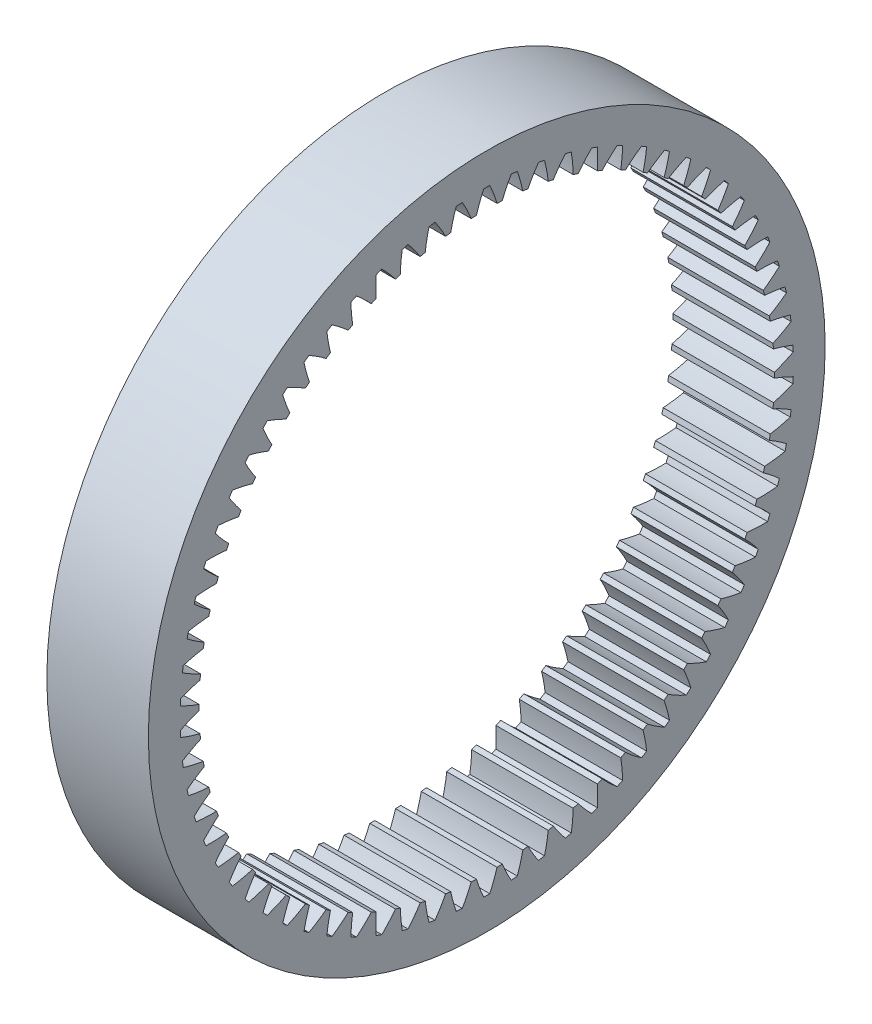
SolidWorks part; units mm, degrees
ref_plane "Plane1" through (0, 0, 0) normal (0, 0, 1) x (1, 0, 0)
ref_plane "Plane2" through (0, 0, 0) normal (0, 1, 0) x (1, 0, 0)
ref_plane "Plane3" through (0, 0, 0) normal (1, 0, 0) x (0, 0, -1)
other "Configuration Table"
sketch "HoldingSke" plane through (0, 0, 0) normal (0, 1, 0) x (1, 0, 0)
  line L0 (0, 0) -> (0.342, -0.9397)
  line L1 (-15, 0) -> (100, 0) construction
  line L2 (0, 0) -> (-2.1039, 2.3779)
  line L3 (0, 0) -> (-11.863, 4.5341)
  line L4 (0, 0) -> (2.9537, 8.1152)
  line L5 (0, 0) -> (-23.7986, -8.8762)
  line L6 (0, 0) -> (-10.5278, -7.1032)
  line L7 (-2.1039, 2.3779) -> (3.3635, 27.1825)
  line L8 (-76.2, 3.3779) -> (-54.61, 3.3779)
  line L9 (-71.009, 38.7566) -> (-53.1078, 45.2721)
  line L10 (-76.2, 71.12) -> (104.1128, 71.12)
  line L11 (0, 0) -> (-12, 0)
  line L12 (-76.2, 101.6) -> (-76.162, 101.6)
  line L13 (24.9733, 27.94) -> (52.9518, 28.4284)
  line L14 (24.9733, 27.94) -> (24.9743, 27.94)
  line L15 (24.9733, 27.94) -> (100.4006, 29.5858)
  circle A0 centre (0, 0) radius 40
  circle A1 centre (0, 0) radius 12.7
  circle A2 centre (0, 0) radius 12.7
  dimension "MHD" = 25.4
  dimension "Hub_dia" = 25.4
  dimension "Diameter" = 80
  dimension "Num_teeth" = 70
  dimension "Pitch" = 1
  dimension "Overall_len" = 25.4
  dimension "Show_teeth" = 70
  dimension "Thickness" = 12.7
  dimension "OAL" = 25.4001
  dimension "T_dim" = 21.59
  dimension "Ap" = 20
  dimension "H" = 19.05
  dimension "Pitch_radius" = 180.3128
  dimension "Width" = 12
  dimension "Backlash" = 0.038
  dimension "Addendum_fac" = 1
  dimension "Dedendum_fac" = 1.25
  dimension "Clearance_fac" = 0.25
  dimension "Dedendum_add" = 0.001
  dimension "Module" = 1
sketch "BasProSke" plane through (0, 0, 0) normal (0, 1, 0) x (1, 0, 0)
  line L0 (-10, 0) -> (60, 0) construction
  line L1 (0, 34) -> (0, 40)
  line L2 (0, 34) -> (12, 34)
  line L3 (12, 34) -> (12, 40)
  line L4 (12, 40) -> (0, 40)
  dimension "Diameter" = 80
  dimension "Thickness" = 12
  dimension "Inside_diameter" = 68
revolve "Base-Revolve" add sketch "BasProSke" angle 360 about L0
sketch "TooCutSke" plane through (0, 0, 0) normal (1, 0, 0) x (0, 0, -1)
  line L3 (0.8803, 34.9889) -> (0.8803, 53.6633) construction
  line L4 (0, 0) -> (0, 59.563) construction
  line L5 (0, 0) -> (-3.0655, 68.2587) construction
  line L6 (-15.5382, 28.9323) -> (36.4767, 31.2683) construction
  circle A0 centre (0, 0) radius 35 construction
  circle A1 centre (0, 0) radius 36.251 construction
  circle A2 centre (0, 0) radius 29.6003 construction
  circle A3 centre (0, 0) radius 33.9746 construction
  arc A4 (1.2263, 33.9525) -> (0.3588, 36.2492) centre (-15.5382, 28.9323) ccw
  arc A5 (1.2263, 33.9525) -> (-1.2263, 33.9525) centre (0, 0) ccw
  arc A6 (0.3588, 36.2492) -> (-0.3588, 36.2492) centre (0, 0) ccw
  arc A7 (-0.3588, 36.2492) -> (-1.2263, 33.9525) centre (15.5382, 28.9323) ccw
  dimension "Pitch_dia" = 70
  dimension "Base_dia" = 59.2006
  dimension "Root_dia" = 72.502
  dimension "Overcut_dia" = 67.9492
  dimension "Flank_rad" = 17.5
  dimension "Half_ang" = 2.571
  dimension "Half_CT" = 0.8803
extrude "ToothCut" cut sketch "TooCutSke" along normal through all
fillet "Breaks" [suppressed] radius 0.1
fillet "RootFillets" [suppressed] radius 0.251
pattern_circular "TeethCuts" count 70 every 5.143 about axis through (-10, 0, 0) along (1, 0, 0) of "RootFillets", "Breaks", "ToothCut"
equation "' \"Module@HoldingSke\" = 6.35"
equation "' \"Num_teeth@HoldingSke\" = 24"
equation "' \"Ap@HoldingSke\" =  14.5"
equation "' \"Ap@HoldingSke\" = 14.5"
equation "' \"Width@HoldingSke\" = 12"
equation "' \"Diameter@HoldingSke\" = 8 * 25.4"
equation "' \"Show_teeth@HoldingSke\" = 100"
equation "' \"Backlash@HoldingSke\" = 0.009 * 25.4"
equation "' \"Addendum_fac@HoldingSke\" = 1.0"
equation "' \"Dedendum_fac@HoldingSke\" = 1.25"
equation "' \"Dedendum_add@HoldingSke\" = 0.00005 * 25.4"
equation "' \"Clearance_fac@HoldingSke\" = 0.25"
equation "\"Pitch@HoldingSke\" = 1 / \"Module@HoldingSke\" "
equation "\"Overcut_dia@TooCutSke\" = (\"Num_teeth@HoldingSke\" - 2 * \"Addendum_fac@HoldingSke\") / \"Pitch@HoldingSke\" - 0.002 * 25.4"
equation "\"Pitch_dia@TooCutSke\" = \"Num_teeth@HoldingSke\" / \"Pitch@HoldingSke\""
equation "\"Base_dia@TooCutSke\" = \"Num_teeth@HoldingSke\" / \"Pitch@HoldingSke\" * cos((\"Ap@HoldingSke\"  * 3.14159265 / 180)) * 0.90"
equation "\"Root_dia@TooCutSke\" = \"Num_teeth@HoldingSke\"  / \"Pitch@HoldingSke\" + 2 *  \"Dedendum_fac@HoldingSke\"/ \"Pitch@HoldingSke\" + \"Dedendum_add@HoldingSke\" * 2"
equation "\"Half_ang@TooCutSke\" = 180 / \"Num_teeth@HoldingSke\""
equation "\"Half_CT@TooCutSke\" = \"Num_teeth@HoldingSke\" / \"Pitch@HoldingSke\" * sin((3.14159265 / 2 / \"Num_teeth@HoldingSke\")) / 2 + 10 * \"Backlash@HoldingSke\" / 4"
equation "\"Flank_rad@TooCutSke\" = \"Num_teeth@HoldingSke\" / \"Pitch@HoldingSke\" / 4"
equation "\"Radius@RootFillets\"= \"Clearance_fac@HoldingSke\" / \"Pitch@HoldingSke\" + \"Dedendum_add@HoldingSke\""
equation "\"Break_rad@Breaks\" = 0.02 / \"Pitch@HoldingSke\" * 5"
equation "\"Num_teeth@TeethCuts\" = int( \"Show_teeth@HoldingSke\" ) + 1"
equation "\"Num_teeth@TeethCuts\" = ((sgn( \"Num_teeth@TeethCuts\" - \"Num_teeth@HoldingSke\" )-1)*( \"Num_teeth@TeethCuts\" - \"Num_teeth@HoldingSke\" ))/-2+ \"Num_teeth@HoldingSke\""
equation "\"Num_teeth@TeethCuts\" = ((sgn( \"Num_teeth@TeethCuts\" - 2.0)+1)*( \"Num_teeth@TeethCuts\" - 2.0))/2 +2.0"
equation "\"Angle@TeethCuts\" = 360.0 / \"Num_teeth@HoldingSke\""
equation "\"Diameter@BasProSke\" = \"Num_teeth@HoldingSke\"  / \"Pitch@HoldingSke\" + 2 *  \"Dedendum_fac@HoldingSke\"/ \"Pitch@HoldingSke\" + \"Dedendum_add@HoldingSke\" * 2 + 0.002 * 25.4"
equation "\"Diameter@BasProSke\" = ((sgn( \"Diameter@BasProSke\"  - \"Diameter@HoldingSke\" )+1)*( \"Diameter@BasProSke\"  - \"Diameter@HoldingSke\" ))/2 + \"Diameter@HoldingSke\""
equation "\"Inside_diameter@BasProSke\" =  (\"Num_teeth@HoldingSke\" - 2 * \"Addendum_fac@HoldingSke\") / \"Pitch@HoldingSke\" "
equation "\"Thickness@BasProSke\"  = \"Width@HoldingSke\""
